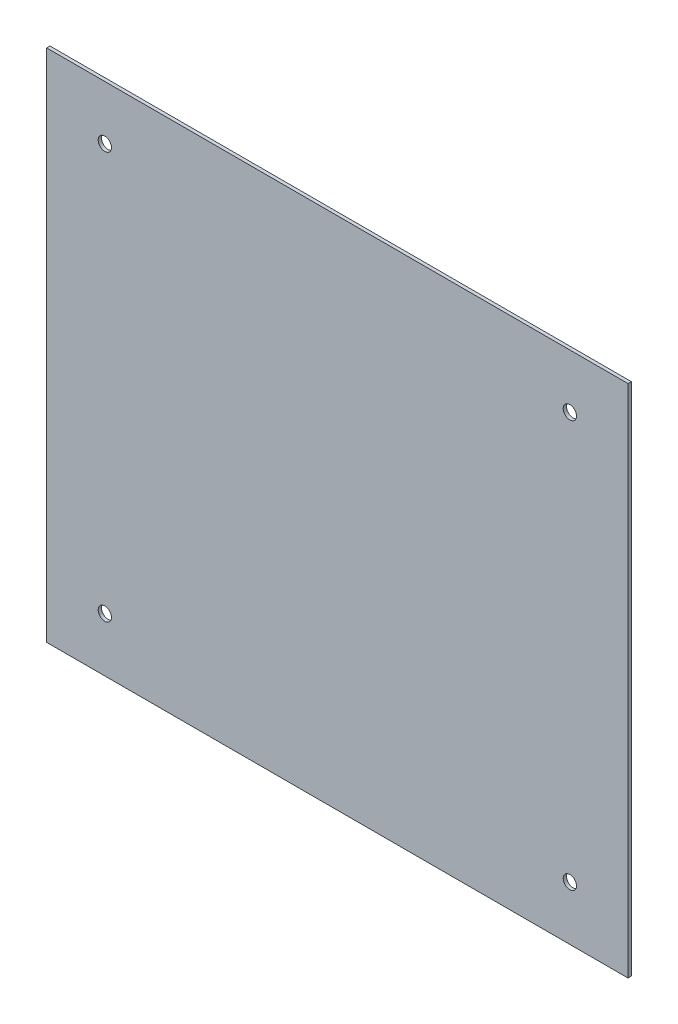
SolidWorks part; units mm, degrees
ref_plane "Front Plane" through (0, 0, 0) normal (0, 0, 1) x (1, 0, 0)
ref_plane "Top Plane" through (0, 0, 0) normal (0, 1, 0) x (1, 0, 0)
ref_plane "Right Plane" through (0, 0, 0) normal (1, 0, 0) x (0, 0, -1)
sketch "Sketch1" plane through (0, 0, 0) normal (0, 0, 1) x (1, 0, 0)
  line L1 (175, -155) -> (-175, -155)
  line L2 (175, -155) -> (175, 155)
  line L3 (175, 155) -> (-175, 155)
  line L4 (-175, -155) -> (-175, 155)
  line L5 (175, -155) -> (-175, 155) construction
  line L6 (175, 155) -> (-175, -155) construction
  point P0 (0, 0)
  dimension "D1" = 350
  dimension "D2" = 310
extrude "Boss-Extrude1" add sketch "Sketch1" along normal blind 2
sketch "Sketch2" plane through (0, 0, 2) normal (0, 0, 1) x (1, 0, 0)
  line L0 (175, 155) -> (-175, 155) construction
  line L1 (-175, 155) -> (-175, -155) construction
  line L2 (0, 155) -> (0, -147.5554) construction
  line L3 (175, 0) -> (-163.6381, 0) construction
  line L4 (175, -155) -> (175, 155) construction
  circle A0 centre (-140, 122.5) radius 4
  circle A1 centre (-140, -122.5) radius 4
  circle A2 centre (140, -122.5) radius 4
  circle A3 centre (140, 122.5) radius 4
  dimension "D1" = 8
  dimension "D2" = 32.5
  dimension "D3" = 35
extrude "Cut-Extrude1" cut sketch "Sketch2" against normal through all
